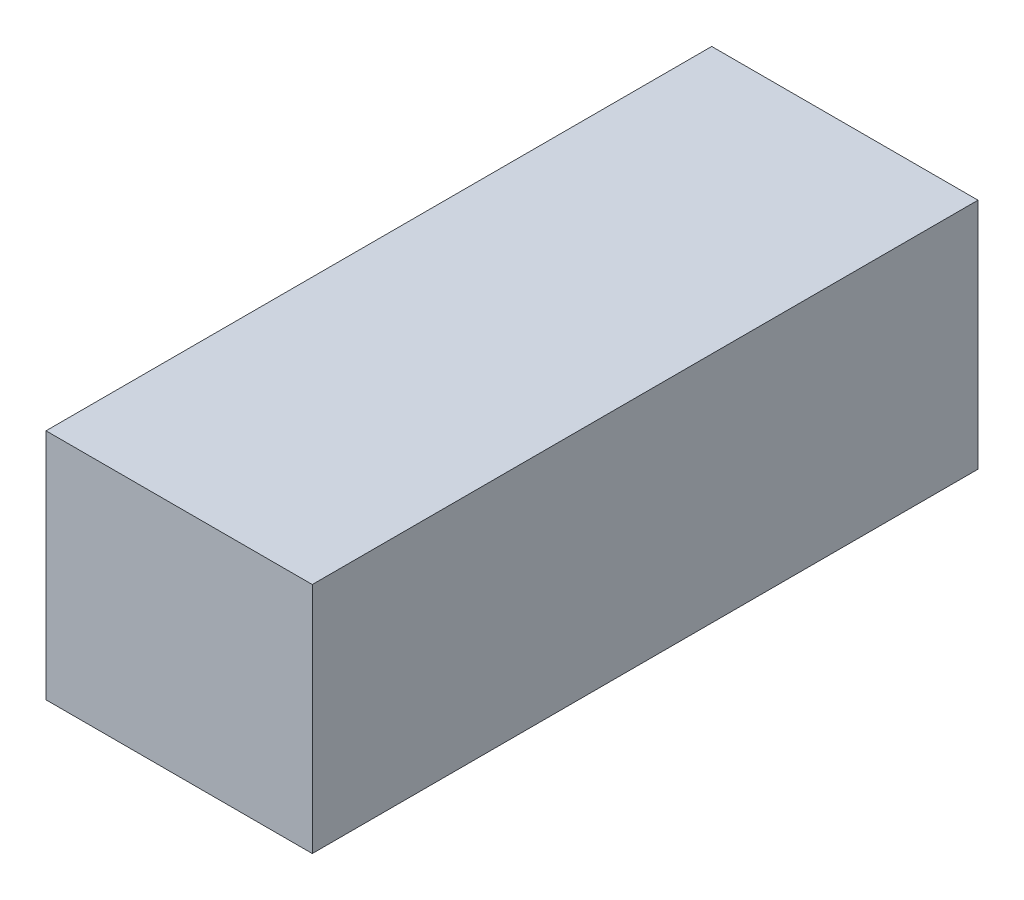
SolidWorks part; units mm, degrees
ref_plane "Front Plane" through (0, 0, 0) normal (0, 0, 1) x (1, 0, 0)
ref_plane "Top Plane" through (0, 0, 0) normal (0, 1, 0) x (1, 0, 0)
ref_plane "Right Plane" through (0, 0, 0) normal (1, 0, 0) x (0, 0, -1)
sketch "Sketch1" plane through (0, 0, 0) normal (0, 0, 1) x (1, 0, 0)
  line L1 (-2, -1.75) -> (2, -1.75)
  line L2 (-2, -1.75) -> (-2, 1.75)
  line L3 (-2, 1.75) -> (2, 1.75)
  line L4 (2, -1.75) -> (2, 1.75)
  line L5 (-2, -1.75) -> (2, 1.75) construction
  line L6 (-2, 1.75) -> (2, -1.75) construction
  point P0 (0, 0)
  dimension "D1" = 4
  dimension "D2" = 3.5
extrude "Boss-Extrude1" add sketch "Sketch1" along normal blind 10
